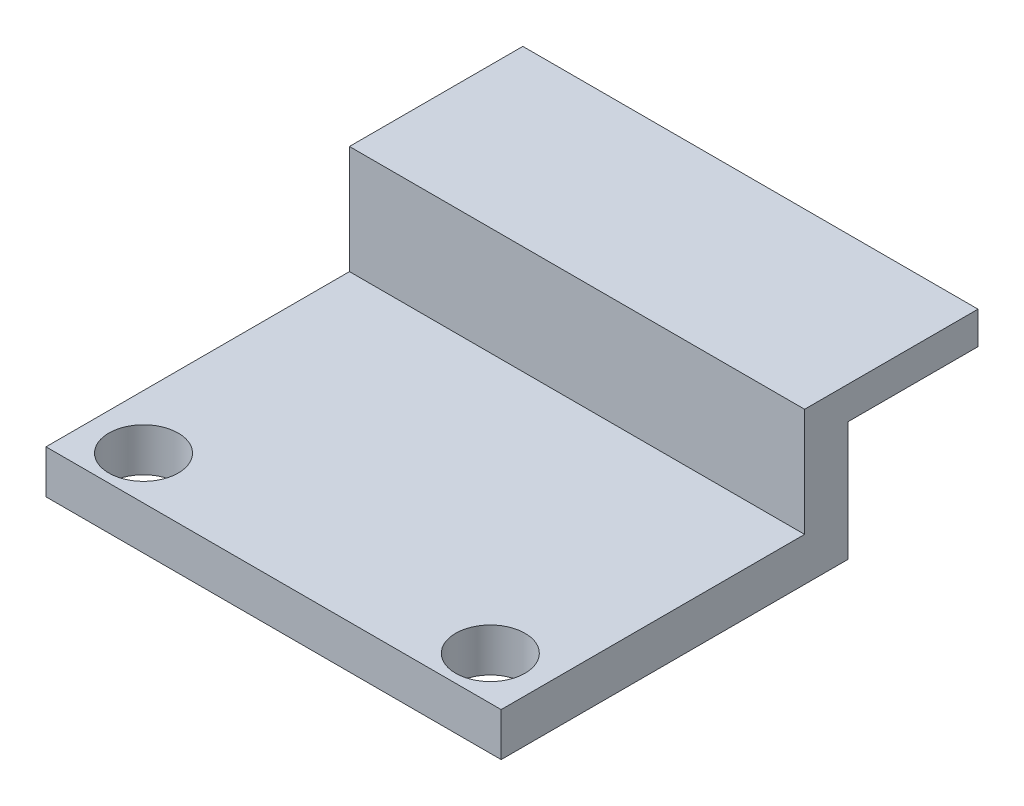
SolidWorks part; units mm, degrees
ref_plane "前视基准面" through (0, 0, 0) normal (0, 0, 1) x (1, 0, 0)
ref_plane "上视基准面" through (0, 0, 0) normal (0, 1, 0) x (1, 0, 0)
ref_plane "右视基准面" through (0, 0, 0) normal (1, 0, 0) x (0, 0, -1)
sketch "草图1" plane through (0, 0, 0) normal (0, 1, 0) x (1, 0, 0)
  line L0 (10.5, 0) -> (10.5, 21.6869) construction
  line L1 (0, 0) -> (21, 0)
  line L2 (0, 0) -> (0, 16)
  line L3 (0, 16) -> (21, 16)
  line L4 (21, 0) -> (21, 16)
  circle A0 centre (18.5, 2) radius 1.6
  circle A1 centre (2.5, 2) radius 1.6
  dimension "D3" = 3.2
  dimension "D4" = 16
  dimension "D5" = 2
  dimension "D1" = 21
  dimension "D2" = 16
extrude "凸台-拉伸1" add sketch "草图1" along normal blind 2
sketch "草图3" plane through (21, 0, 0) normal (1, 0, 0) x (0, 0, -1)
  line L0 (16, 2) -> (14, 2)
  line L1 (0, 2) -> (16, 2) construction
  line L2 (14, 2) -> (14, 7)
  line L3 (14, 7) -> (22, 7)
  line L4 (22, 7) -> (22, 5.5)
  line L5 (22, 5.5) -> (16, 5.5)
  line L6 (16, 5.5) -> (16, 2)
  dimension "D1" = 2
  dimension "D2" = 5
  dimension "D3" = 1.5
  dimension "D4" = 6
extrude "凸台-拉伸2" add sketch "草图3" against normal blind 21
